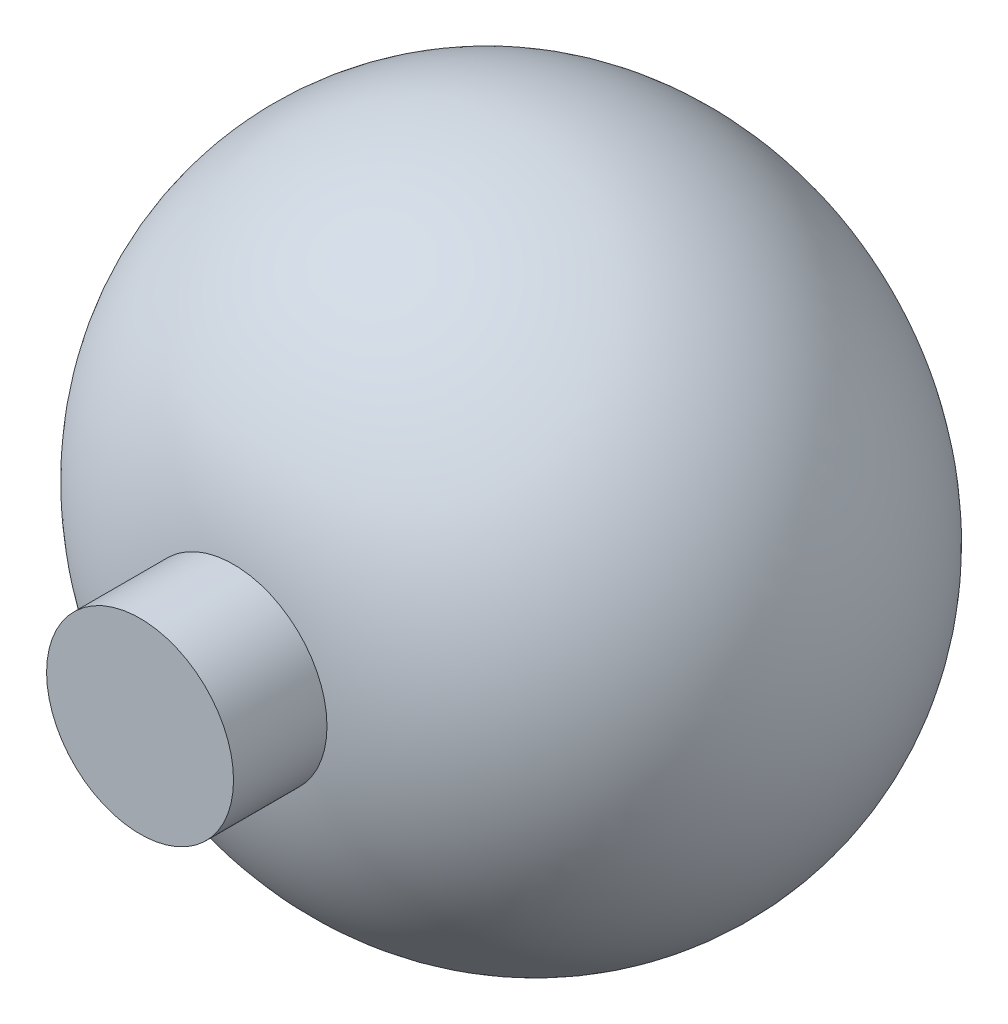
SolidWorks part; units mm, degrees
ref_plane "Front Plane" through (0, 0, 0) normal (0, 0, 1) x (1, 0, 0)
ref_plane "Top Plane" through (0, 0, 0) normal (0, 1, 0) x (1, 0, 0)
ref_plane "Right Plane" through (0, 0, 0) normal (1, 0, 0) x (0, 0, -1)
sketch "Sketch1" plane through (0, 0, 0) normal (0, 1, 0) x (1, 0, 0)
  line L0 (0, 34.6993) -> (0, 0)
  line L1 (0, 0) -> (-5, 0)
  line L2 (-5, 0) -> (-5, 5)
  line L3 (0, 34.6993) -> (-5, 34.6993)
  arc A0 (-5, 5) -> (-5, 34.6993) centre (-2.8817, 19.8497) cw
revolve "Revolve1" add sketch "Sketch1" angle 360 about L0
